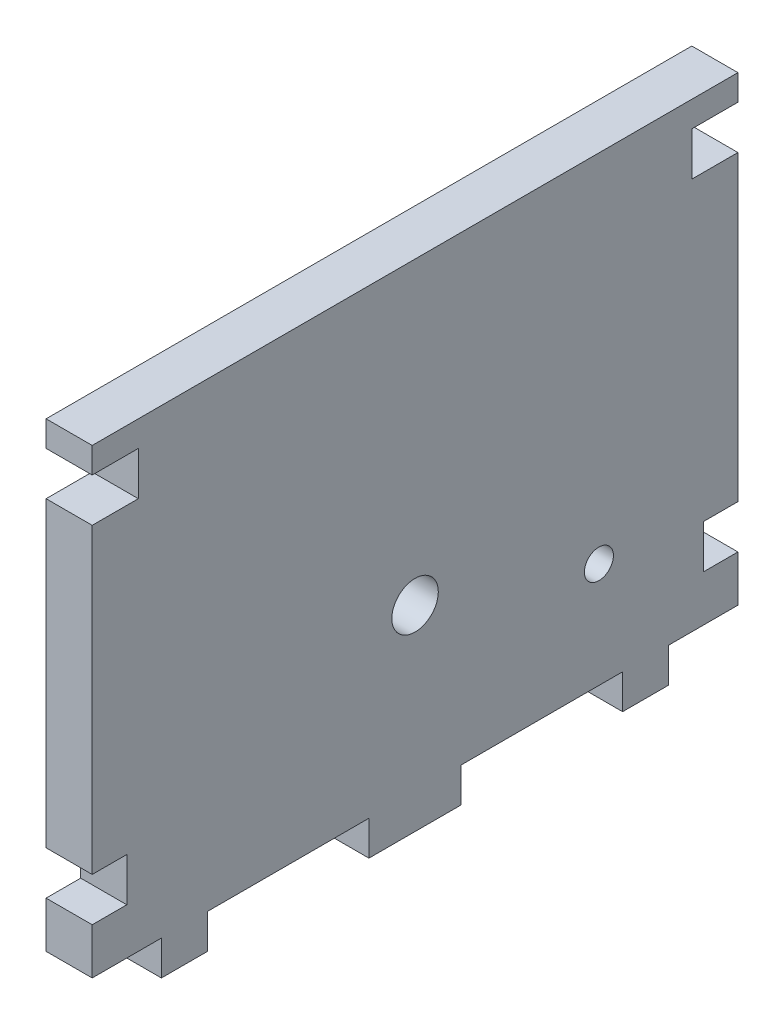
SolidWorks part; units mm, degrees
ref_plane "Front Plane" through (0, 0, 0) normal (0, 0, 1) x (1, 0, 0)
ref_plane "Top Plane" through (0, 0, 0) normal (0, 1, 0) x (1, 0, 0)
ref_plane "Right Plane" through (0, 0, 0) normal (1, 0, 0) x (0, 0, -1)
sketch "Sketch1" plane through (0, 0, 0) normal (1, 0, 0) x (0, 0, -1)
  line L0 (28.575, -26.9875) -> (28.575, -22.225)
  line L1 (44.45, -22.225) -> (-44.45, -22.225)
  line L2 (44.45, -22.225) -> (44.45, 22.225)
  line L3 (44.45, 22.225) -> (-44.45, 22.225)
  line L4 (-44.45, -22.225) -> (-44.45, 22.225)
  line L5 (0, 22.225) -> (0, -22.225) construction
  line L6 (44.45, 0) -> (-44.45, 0) construction
  line L7 (6.35, -26.9875) -> (-6.35, -26.9875)
  line L8 (6.35, -26.9875) -> (6.35, -22.225)
  line L9 (6.35, -22.225) -> (-6.35, -22.225)
  line L10 (-6.35, -26.9875) -> (-6.35, -22.225)
  line L11 (0, -22.225) -> (0, -26.9875) construction
  line L12 (6.35, -24.6062) -> (-6.35, -24.6062) construction
  line L13 (-28.575, -26.9875) -> (-34.925, -26.9875)
  line L14 (-28.575, -26.9875) -> (-28.575, -22.225)
  line L15 (-28.575, -22.225) -> (-34.925, -22.225)
  line L16 (-34.925, -26.9875) -> (-34.925, -22.225)
  line L17 (-31.75, -22.225) -> (-31.75, -26.9875) construction
  line L18 (-28.575, -24.6062) -> (-34.925, -24.6062) construction
  line L19 (28.575, -22.225) -> (34.925, -22.225)
  line L20 (34.925, -26.9875) -> (34.925, -22.225)
  line L21 (28.575, -26.9875) -> (34.925, -26.9875)
  line L22 (-44.45, 41.275) -> (44.45, 41.275)
  line L23 (39.6875, -15.875) -> (39.6875, -9.8806)
  line L24 (39.6875, -9.8806) -> (44.45, -9.8806)
  line L25 (-44.45, -9.8806) -> (-39.6875, -9.8806)
  line L26 (-39.6875, -9.8806) -> (-39.6875, -15.875)
  line L27 (-44.45, 41.275) -> (-44.45, 22.225)
  line L28 (-44.45, 22.225) -> (-43.6191, 22.0477)
  line L29 (44.45, 41.275) -> (44.45, 22.225)
  line L30 (39.6875, -15.875) -> (44.45, -15.875)
  line L31 (-39.6875, -15.875) -> (-44.45, -15.875)
  line L33 (44.45, 37.7444) -> (38.1, 37.7444)
  line L34 (44.45, 37.7444) -> (44.45, 31.75)
  line L35 (44.45, 31.75) -> (38.1, 31.75)
  line L36 (38.1, 37.7444) -> (38.1, 31.75)
  line L37 (-44.45, 37.7444) -> (-38.1, 37.7444)
  line L38 (-44.45, 37.7444) -> (-44.45, 31.75)
  line L39 (-44.45, 31.75) -> (-38.1, 31.75)
  line L40 (-38.1, 37.7444) -> (-38.1, 31.75)
  circle A0 centre (0, 0) radius 3.2004
  circle A1 centre (25.3091, -7.7249) radius 2
  point P0 (0, 0)
  point P4 (0, -24.6062)
  point P8 (-31.75, -24.6062)
  dimension "D7" = 6.4008
  dimension "D8" = 4
  dimension "D1" = 4.7625
  dimension "D2" = 6.35
  dimension "D3" = 12.7
  dimension "D4" = 57.15
  dimension "D5" = 44.45
  dimension "D6" = 88.9
  dimension "D9" = 25.3091
  dimension "D10" = 7.7249
  dimension "D11" = 63.5
  dimension "D12" = 5.9944
  dimension "D13" = 4.7625
  dimension "D14" = 6.35
  dimension "D15" = 9.525
  dimension "D16" = 5.9944
  dimension "D17" = 6.35
extrude "Boss-Extrude1" add sketch "Sketch1" along normal blind 6.35 contours L4 L1 L2 L3 A1 A0 | L0 L21 L20 L1 | L10 L7 L8 L1 | L16 L13 L14 L1 | L29 L22 L27 L3
sketch "Sketch2" plane through (6.35, 0, 0) normal (1, 0, 0) x (0, 0, -1)
  line L0 (-44.45, -22.225) -> (-44.45, -15.875) construction
  line L1 (-38.1, -9.525) -> (-44.45, -9.525)
  line L2 (-38.1, -9.525) -> (-38.1, 3.175)
  line L3 (-38.1, 3.175) -> (-44.45, 3.175)
  line L4 (-44.45, -9.525) -> (-44.45, 3.175)
  line L5 (-41.275, 3.175) -> (-41.275, -9.525) construction
  line L6 (-38.1, -3.175) -> (-44.45, -3.175) construction
  line L7 (-34.925, -22.225) -> (-44.45, -22.225) construction
  line L8 (0, 0) -> (0, 19.6541) construction
  line L9 (38.1, -9.525) -> (44.45, -9.525)
  line L10 (44.45, -9.525) -> (44.45, 3.175)
  line L11 (38.1, 3.175) -> (44.45, 3.175)
  line L12 (38.1, -9.525) -> (38.1, 3.175)
  point P0 (-41.275, -3.175)
  dimension "D1" = 6.35
  dimension "D2" = 12.7
  dimension "D3" = 12.7
extrude "Cut-Extrude1" [suppressed] cut sketch "Sketch2" against normal blind 6.35
equation "\"D2@Sketch1\"=.25"
equation "\"D3@Sketch1\"=.5"
